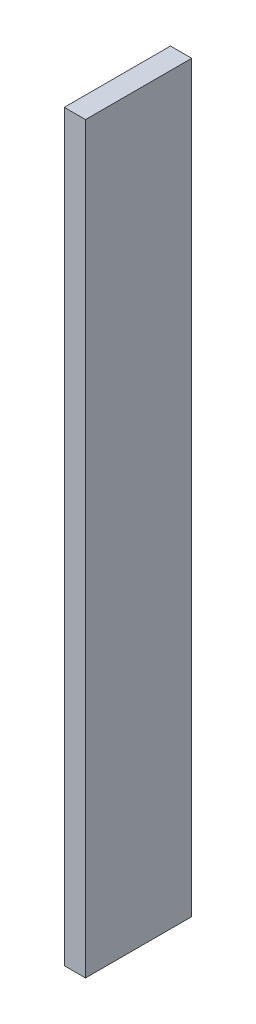
SolidWorks part; units mm, degrees
ref_plane "Front Plane" through (0, 0, 0) normal (0, 0, 1) x (1, 0, 0)
ref_plane "Top Plane" through (0, 0, 0) normal (0, 1, 0) x (1, 0, 0)
ref_plane "Right Plane" through (0, 0, 0) normal (1, 0, 0) x (0, 0, -1)
sketch "Sketch3" plane through (0, 0, 0) normal (0, 0, 1) x (1, 0, 0)
  line L1 (0, 0) -> (10, 0)
  line L2 (0, 0) -> (0, 350)
  line L3 (0, 350) -> (10, 350)
  line L4 (10, 0) -> (10, 350)
  dimension "D1" = 350
  dimension "D2" = 10
extrude "Boss-Extrude2" add sketch "Sketch3" along normal blind 50
sketch "Sketch4" plane through (0, 0, 0) normal (0, 0, -1) x (-1, 0, 0)
  line L0 (0, 0) -> (-10, 0) construction
  line L1 (-10, 350) -> (0, 350) construction
  line L2 (-10, 0) -> (-10, 350) construction
  circle A0 centre (-5, 330) radius 1.4
  circle A1 centre (-5, 20) radius 1.4
  dimension "D1" = 2.8
  dimension "D2" = 2.8
  dimension "D3" = 20
  dimension "D4" = 20
  dimension "D5" = 5
  dimension "D6" = 5
extrude "Cut-Extrude2" cut sketch "Sketch4" against normal blind 10
